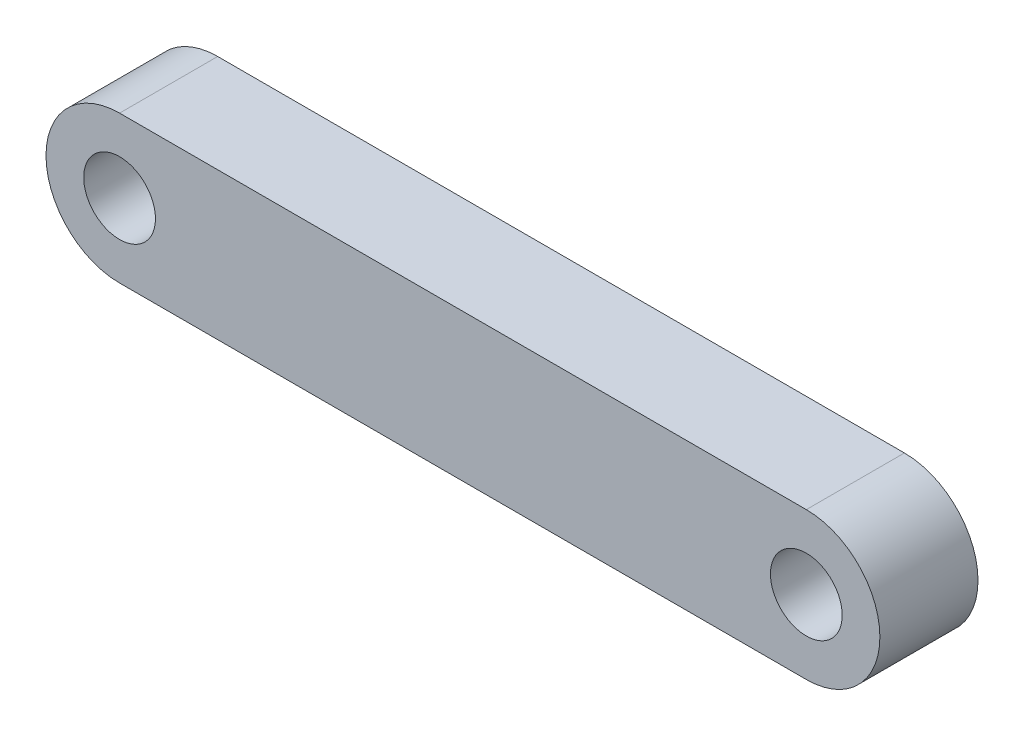
SolidWorks part; units mm, degrees
ref_plane "Front Plane" through (0, 0, 0) normal (0, 0, 1) x (1, 0, 0)
ref_plane "Top Plane" through (0, 0, 0) normal (0, 1, 0) x (1, 0, 0)
ref_plane "Right Plane" through (0, 0, 0) normal (1, 0, 0) x (0, 0, -1)
sketch "Sketch1" plane through (0, 0, 0) normal (0, 0, 1) x (1, 0, 0)
  line L0 (0, 0) -> (70, 0) construction
  line L1 (0, 7.5) -> (70, 7.5)
  line L2 (0, -7.5) -> (70, -7.5)
  arc A0 (0, 7.5) -> (0, -7.5) centre (0, 0) ccw
  arc A1 (70, -7.5) -> (70, 7.5) centre (70, 0) ccw
  circle A2 centre (0, 0) radius 3.6576
  circle A3 centre (70, 0) radius 3.6576
  point P3 (35, 0)
  dimension "D3" = 7.3152
  dimension "D1" = 70
  dimension "D2" = 15
extrude "Boss-Extrude1" add sketch "Sketch1" along normal blind 10
